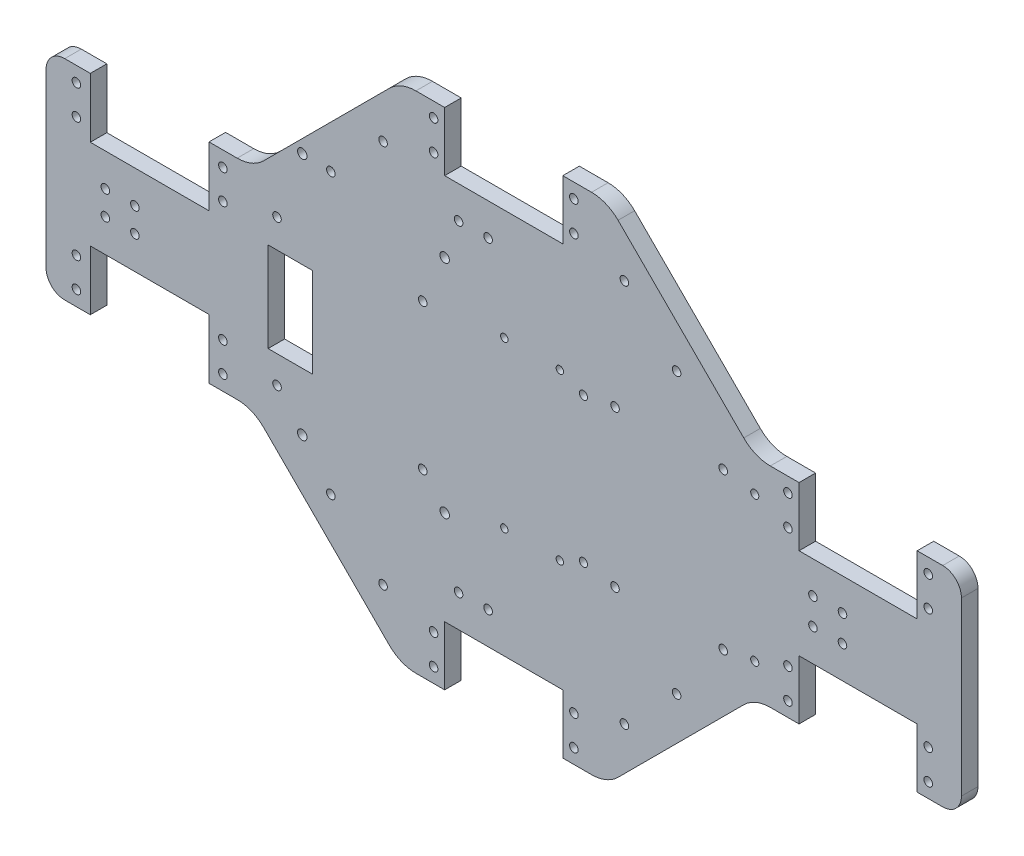
SolidWorks part; units mm, degrees
material "ABS"
ref_plane "Front" through (0, 0, 0) normal (0, 0, 1) x (1, 0, 0)
ref_plane "Top" through (0, 0, 0) normal (0, 1, 0) x (1, 0, 0)
ref_plane "Right" through (0, 0, 0) normal (1, 0, 0) x (0, 0, -1)
sketch "Esquisse1" plane through (0, 0, 0) normal (0, 0, 1) x (1, 0, 0)
  line L0 (70, -35.4) -> (120, -85.4)
  line L1 (0, 0) -> (25.8386, 0)
  line L2 (0, 0) -> (0, -35.4)
  line L3 (0, -35.4) -> (70, -35.4)
  line L5 (0, 0) -> (70, -35.4) construction
  line L6 (0, -35.4) -> (25.8386, 0) construction
  line L7 (120, -85.4) -> (190, -85.4)
  line L8 (190, -85.4) -> (240, -35.4)
  line L9 (240, -35.4) -> (310, -35.4)
  line L10 (310, -35.4) -> (310, 0)
  line L11 (310, 0) -> (25.8386, 0)
  point P0 (0, 0)
  dimension "D1" = 70
  dimension "D2" = 70
  dimension "D3" = 70
  dimension "D4" = 135
  dimension "D5" = 135
  dimension "D6" = 0
  dimension "D7" = 50
  dimension "D8" = 35.4
extrude "Boss.-Extru.1" add sketch "Esquisse1" along normal blind 5.6
sketch "Esquisse2" plane through (0, 0, 5.6) normal (0, 0, 1) x (1, 0, 0)
  line L0 (0, -35.4) -> (70, -35.4) construction
  line L1 (15, -15.2) -> (55.2, -15.2)
  line L2 (15, -15.2) -> (15, -35.4)
  line L3 (15, -35.4) -> (55.2, -35.4)
  line L4 (55.2, -15.2) -> (55.2, -35.4)
  line L5 (15, -15.2) -> (55.2, -35.4) construction
  line L6 (15, -35.4) -> (55.2, -15.2) construction
  line L7 (0, 0) -> (0, -35.4) construction
  point P0 (0, -90)
  dimension "D1" = 20.2
  dimension "D2" = 40.2
  dimension "D3" = 15
extrude "Enlèv. mat.-Extru.1" cut sketch "Esquisse2" against normal up to next
sketch "Esquisse3" plane through (0, 0, 5.6) normal (0, 0, 1) x (1, 0, 0)
  line L0 (15, -25.3) -> (55.2, -25.3) construction
  line L1 (15, -15.2) -> (15, -35.4) construction
  line L2 (55.2, -35.4) -> (55.2, -15.2) construction
  line L3 (55.2, -15.2) -> (15, -15.2) construction
  circle A0 centre (10.3, -30.3) radius 1.45
  circle A1 centre (59.9, -30.3) radius 1.45
  circle A2 centre (59.9, -20.3) radius 1.45
  circle A3 centre (10.3, -20.3) radius 1.45
  circle A4 centre (20.1, -4.1) radius 1.45
  circle A5 centre (30.1, -4.1) radius 1.45
  dimension "D1" = 4.7
  dimension "D2" = 5
  dimension "D3" = 5
  dimension "D4" = 2.9
  dimension "D5" = 4.7
  dimension "D6" = 2.9
  dimension "D7" = 2.9
  dimension "D8" = 10
  dimension "D9" = 5.1
  dimension "D10" = 11.1
  dimension "D11" = 0
extrude "Enlèv. mat.-Extru.2" cut sketch "Esquisse3" against normal up to next
sketch "Sketch2" plane through (0, 0, 0) normal (0, 0, 1) x (1, 0, 0)
  line L0 (120, -85.4) -> (190, -85.4) construction
  line L1 (255, -15.4) -> (295, -15.4)
  line L2 (255, -15.4) -> (255, -35.4)
  line L3 (255, -35.4) -> (295, -35.4)
  line L4 (295, -15.4) -> (295, -35.4)
  line L5 (255, -15.4) -> (295, -35.4) construction
  line L6 (255, -35.4) -> (295, -15.4) construction
  line L7 (240, -35.4) -> (310, -35.4) construction
  line L8 (310, -35.4) -> (310, 0) construction
  line L9 (135, -65.4) -> (175, -65.4)
  line L10 (135, -65.4) -> (135, -85.4)
  line L11 (135, -85.4) -> (175, -85.4)
  line L12 (175, -65.4) -> (175, -85.4)
  line L13 (135, -65.4) -> (175, -85.4) construction
  line L14 (135, -85.4) -> (175, -65.4) construction
  point P0 (0, -90)
  point P11 (-35, 0)
  dimension "D1" = 20
  dimension "D2" = 40
  dimension "D3" = 15
  dimension "D4" = 40
  dimension "D5" = 20
  dimension "D6" = 15
extrude "Cut-Extrude2" cut sketch "Sketch2" against normal through all and the other way through all
sketch "Sketch5" plane through (0, 0, 0) normal (0, 0, 1) x (1, 0, 0)
  line L0 (180, -75.4) -> (175, -75.4) construction
  line L1 (175, -85.4) -> (175, -65.4) construction
  line L2 (255, -25.4) -> (295, -25.4) construction
  line L4 (295, -35.4) -> (295, -15.4) construction
  line L5 (255, -15.4) -> (255, -35.4) construction
  circle A0 centre (131.25, -80.48) radius 1.45
  circle A1 centre (178.75, -80.48) radius 1.45
  circle A2 centre (178.75, -70.32) radius 1.45
  circle A3 centre (131.25, -70.32) radius 1.45
  circle A4 centre (251.25, -30.48) radius 1.45
  circle A5 centre (298.75, -30.48) radius 1.45
  circle A6 centre (298.75, -20.32) radius 1.45
  circle A7 centre (251.25, -20.32) radius 1.45
  circle A8 centre (139.712, -54.49) radius 1.45
  circle A9 centre (149.712, -54.49) radius 1.45
  circle A10 centre (259.712, -4.49) radius 1.45
  circle A11 centre (269.712, -4.49) radius 1.45
  dimension "D1" = 5.08
  dimension "D2" = 5.08
  dimension "D3" = 47.5
  dimension "D4" = 2.9
  dimension "D5" = 3.75
  dimension "D10" = 2.9
  dimension "D11" = 2.9
  dimension "D12" = 2.9
  dimension "D16" = 2.9
  dimension "D17" = 2.9
  dimension "D6" = 5.08
  dimension "D7" = 5.08
  dimension "D8" = 3.75
  dimension "D9" = 3.75
  dimension "D13" = 10
  dimension "D14" = 8.462
  dimension "D15" = 15.83
  dimension "D18" = 8.462
  dimension "D19" = 15.83
  dimension "D20" = 10
  dimension "D21" = 0
  dimension "D22" = 0
extrude "Cut-Extrude4" cut sketch "Sketch5" along normal through all
mirror "Mirror1" about plane through (0, 0, 0) normal (0, 1, 0) of "Cut-Extrude4", "Cut-Extrude2", "Enlèv. mat.-Extru.1", "Enlèv. mat.-Extru.2", "Boss.-Extru.1"
sketch "Esquisse4" plane through (0, 0, 5.6) normal (0, 0, 1) x (1, 0, 0)
  line L0 (182, 24.5) -> (240, 24.5) construction
  line L1 (240, 24.5) -> (240, -24.5) construction
  line L2 (240, -24.5) -> (182, -24.5) construction
  line L3 (0, 0) -> (310, 0) construction
  line L4 (0, 35.4) -> (0, -35.4) construction
  line L5 (310, -35.4) -> (310, 35.4) construction
  line L6 (255, 15.4) -> (255, 35.4) construction
  circle A0 centre (182, -24.5) radius 1.375
  circle A4 centre (240, -24.5) radius 1.375
  circle A5 centre (240, 24.5) radius 1.375
  circle A6 centre (182, 24.5) radius 1.375
  point P14 (240, 0)
  dimension "D1" = 2.75
  dimension "D6" = 15
  dimension "D2" = 2
  dimension "D3" = 58
  dimension "D4" = 49
  dimension "D5" = 2
extrude "Enlèv. mat.-Extru.4" cut sketch "Esquisse4" against normal through all
sketch "Esquisse6" plane through (0, 0, 0) normal (0, 0, -1) x (-1, 0, 0)
  line L0 (0, 0) -> (-385.37, 0) construction
  line L1 (-229.315, 26.415) -> (-192.685, 26.415) construction
  line L2 (-192.685, 26.415) -> (-192.685, -26.415) construction
  line L3 (-192.685, -26.415) -> (-229.315, -26.415) construction
  line L4 (-182, 24.5) -> (-240, 24.5) construction
  line L5 (-211, 24.5) -> (-211, 26.415) construction
  circle A0 centre (-192.685, -26.415) radius 1.45
  circle A4 centre (-229.315, -26.415) radius 1.45
  circle A5 centre (-229.315, 26.415) radius 1.45
  circle A6 centre (-192.685, 26.415) radius 1.45
  point P5 (-192.685, 0)
  dimension "D1" = 2.9
  dimension "D2" = 2
  dimension "D3" = 36.63
  dimension "D4" = 52.83
  dimension "D5" = 2
extrude "Enlèv. mat.-Extru.6" cut sketch "Esquisse6" against normal through all
sketch "Esquisse8" plane through (0, 0, 0) normal (0, 0, -1) x (-1, 0, 0)
  line L0 (-174, 27.95) -> (-155.2, 27.95) construction
  line L1 (-155.2, 27.95) -> (-155.2, -27.95) construction
  line L2 (-155.2, -27.95) -> (-174, -27.95) construction
  line L3 (0, 0) -> (-310, 0) construction
  line L4 (-310, -35.4) -> (-310, 35.4) construction
  line L5 (-55.2, 35.4) -> (-55.2, 15.2) construction
  circle A0 centre (-155.2, 27.95) radius 1.25
  circle A1 centre (-174, 27.95) radius 1.25
  circle A2 centre (-174, -27.95) radius 1.25
  circle A3 centre (-155.2, -27.95) radius 1.25
  point P16 (-155.2, 0)
  dimension "D1" = 2.5
  dimension "D2" = 18.8
  dimension "D3" = 55.9
  dimension "D6" = 100
  dimension "D4" = 2
  dimension "D5" = 2
extrude "Enlèv. mat.-Extru.7" cut sketch "Esquisse8" against normal through all
sketch "Esquisse9" plane through (0, 0, 0) normal (0, 0, -1) x (-1, 0, 0)
  line L0 (-135, 65.4) -> (-135, 85.4) construction
  line L2 (-175, 65.4) -> (-135, 65.4) construction
  circle A1 centre (-135, -33.48) radius 1.6
  circle A2 centre (-86.78, -34.71) radius 1.6
  circle A3 centre (-86.78, 47.76) radius 1.6
  circle A4 centre (-135, 41.4) radius 1.6
  dimension "D8" = 1.23
  dimension "D1" = 74.88
  dimension "D2" = 82.47
  dimension "D3" = 48.22
  dimension "D4" = 48.22
  dimension "D5" = 48.22
  dimension "D6" = 24
extrude "Enlèv. mat.-Extru.8" cut sketch "Esquisse9" against normal through all
sketch "Sketch6" plane through (0, 0, 5.6) normal (0, 0, 1) x (1, 0, 0)
  line L0 (0, 0) -> (310, 0) construction
  line L1 (75.2, -15.2) -> (90.2, -15.2)
  line L2 (75.2, -15.2) -> (75.2, 15.2)
  line L3 (75.2, 15.2) -> (90.2, 15.2)
  line L4 (90.2, -15.2) -> (90.2, 15.2)
  line L5 (310, -35.4) -> (310, 35.4) construction
  line L6 (55.2, 15.2) -> (15, 15.2) construction
  line L7 (55.2, 35.4) -> (55.2, 15.2) construction
  point P9 (75.2, 0)
  dimension "D1" = 20
  dimension "D2" = 15
extrude "Cut-Extrude5" cut sketch "Sketch6" against normal blind 10
ref_plane "Plan1" through (155, 0, 0) normal (-1, 0, 0) x (0, 0, 1)
ref_plane "Plan2" through (0, 0, 0) normal (0, 1, 0) x (1, 0, 0)
sketch "Esquisse12" plane through (0, 0, 5.6) normal (0, 0, 1) x (1, 0, 0)
  line L0 (96.4645, 47.3223) -> (114.1421, 65) construction
  line L1 (155, 24.0954) -> (155, -24.0954) construction
  line L2 (22.5792, 0) -> (-22.5792, 0) construction
  line L3 (70, 35.4) -> (120, 85.4) construction
  line L4 (135, 65.4) -> (135, 85.4) construction
  line L5 (175, 65.4) -> (135, 65.4) construction
  circle A0 centre (114.1421, 65) radius 1.45
  circle A1 centre (96.4645, 47.3223) radius 1.45
  circle A2 centre (213.5355, 47.3223) radius 1.45
  circle A3 centre (195.8579, 65) radius 1.45
  circle A4 centre (213.5355, -47.3223) radius 1.45
  circle A5 centre (195.8579, -65) radius 1.45
  circle A6 centre (114.1421, -65) radius 1.45
  circle A7 centre (96.4645, -47.3223) radius 1.45
  point P4 (0, 0)
  point P25 (114.1421, 64.0426)
  dimension "D1" = 2.9
  dimension "D2" = 2.9
  dimension "D3" = 25
  dimension "D4" = 20.8579
  dimension "D5" = 0.4
extrude "Enlèv. mat.-Extru.11" cut sketch "Esquisse12" against normal through all
fillet "Fillet1" radius 6.35 4 edges at (310, 35.4, 2.8) (310, -35.4, 2.8) (0, -35.4, 2.8) (0, 35.4, 2.8)
fillet "Fillet2" radius 12.7 8 edges at (120, -85.4, 2.8) (70, -35.4, 2.8) (190, -85.4, 2.8) (240, -35.4, 2.8) (240, 35.4, 2.8) (190, 85.4, 2.8) (120, 85.4, 2.8) (70, 35.4, 2.8)
sketch "Sketch8" plane through (0, 0, 5.6) normal (0, 0, 1) x (1, 0, 0)
  circle A0 centre (78.2267, 24.875) radius 1.45
  circle A1 centre (127.5767, 24.875) radius 1.45
  circle A2 centre (127.5767, -24.475) radius 1.45
  circle A3 centre (78.2267, -24.475) radius 1.45
  dimension "D1" = 2.9
  dimension "D2" = 2.9
  dimension "D3" = 2.9
  dimension "D4" = 2.9
extrude "Cut-Extrude7" cut sketch "Sketch8" against normal through all
